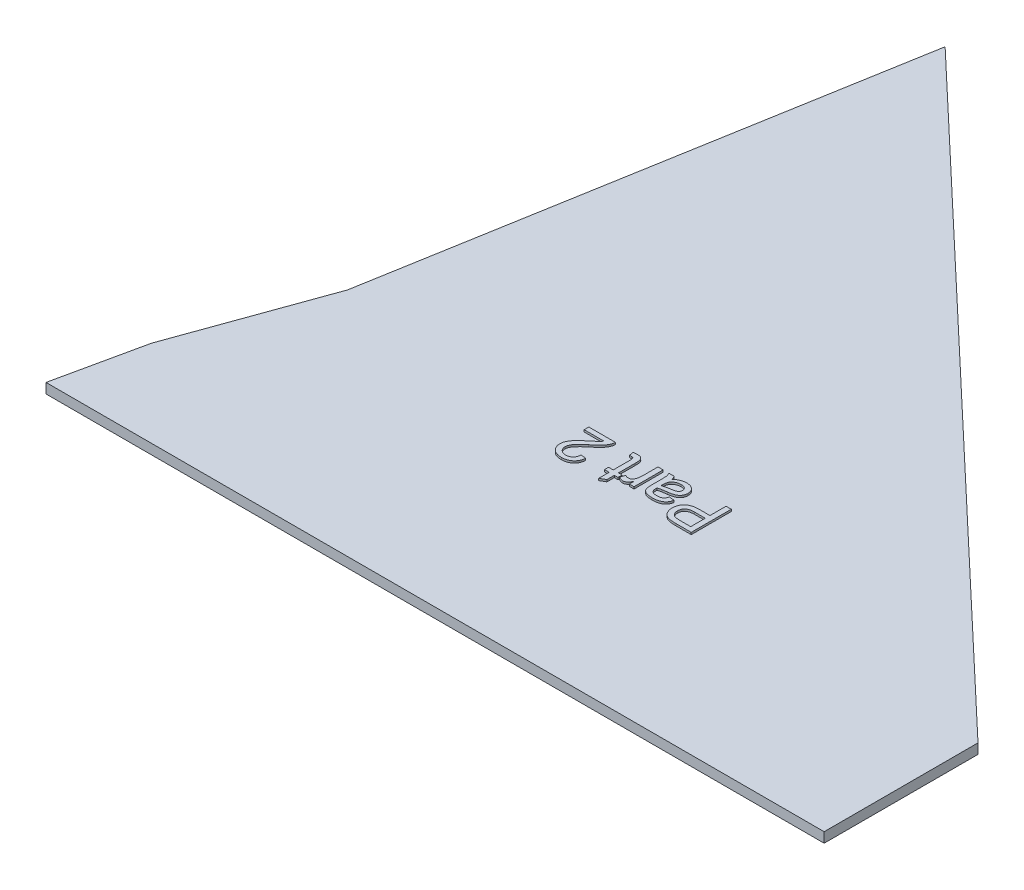
SolidWorks part; units mm, degrees
ref_plane "前视基准面" through (0, 0, 0) normal (0, 0, 1) x (1, 0, 0)
ref_plane "上视基准面" through (0, 0, 0) normal (0, 1, 0) x (1, 0, 0)
ref_plane "右视基准面" through (0, 0, 0) normal (1, 0, 0) x (0, 0, -1)
other "Configuration Table"
sketch "草图1" plane through (0, 0, 0) normal (0, 1, 0) x (1, 0, 0)
  line L0 (0, 0) -> (63.5515, -60.177) construction
  line L1 (63.5515, -60.177) -> (63.5515, -67.0349) construction
  line L2 (63.5515, -67.0349) -> (-14.2949, -67.0349) construction
  line L3 (-14.2949, -67.0349) -> (-9.1207, -52.6598) construction
  line L4 (-9.1207, -52.6598) -> (0, 0) construction
  line L5 (0.667, -2.0087) -> (62.5515, -60.6072)
  line L6 (62.5515, -60.6072) -> (62.5515, -66.0349)
  line L8 (-12.8722, -66.0349) -> (-8.1503, -52.9164)
  line L9 (-8.1503, -52.9164) -> (0.667, -2.0087)
  line L10 (62.5515, -66.0349) -> (-12.8722, -66.0349) construction
  line L11 (-14.2949, -67.0349) -> (-16.4485, -76.9805) construction
  line L12 (-16.4485, -76.9805) -> (40.0455, -76.9805) construction
  line L13 (40.0455, -76.9805) -> (40.0455, -74.9805) construction
  line L14 (40.0455, -74.9805) -> (63.5515, -74.9805) construction
  line L15 (63.5515, -74.9805) -> (63.5515, -67.0349) construction
  line L16 (-12.8722, -66.0349) -> (-13.2321, -67.0349)
  line L18 (-13.3176, -67.2465) -> (-15.2088, -75.9805)
  line L19 (-15.2088, -75.9805) -> (39.0455, -75.9805)
  line L22 (62.5515, -73.9805) -> (62.5515, -67.0349)
  line L23 (-13.3176, -67.2465) -> (-13.2321, -67.0349)
  line L24 (62.5515, -66.0349) -> (62.5515, -67.0349)
  line L25 (39.0455, -73.9805) -> (62.5515, -73.9805) construction
  line L26 (39.0455, -75.9805) -> (39.0455, -73.9805) construction
  line L27 (62.5515, -73.9805) -> (62.5515, -75.9805)
  line L28 (62.5515, -75.9805) -> (39.0455, -75.9805)
  dimension "D1" = 87.5218
  dimension "D2" = 6.8579
  dimension "D3" = 77.8464
  dimension "D4" = 15.278
  dimension "D5" = 53.4438
  dimension "D6" = 5.1742
  dimension "D8" = 10.1761
  dimension "D9" = 56.494
  dimension "D10" = 2
  dimension "D11" = 23.506
  dimension "D12" = 1
  dimension "D7" = 1
extrude "凸台-拉伸2" add sketch "草图1" along normal blind 1
sketch "草图2" plane through (0, 1, 0) normal (0, -1, 0) x (1, 0, 0)
  line L0 (-8.1503, 52.9164) -> (54.4294, 52.9164) construction
  line L1 (62.5515, 60.6072) -> (0.667, 2.0087) construction
  text T0 "Part 2" font "@Arial Unicode MS" height 4
extrude "凸台-拉伸3" add sketch "草图2" against normal blind 0.2
